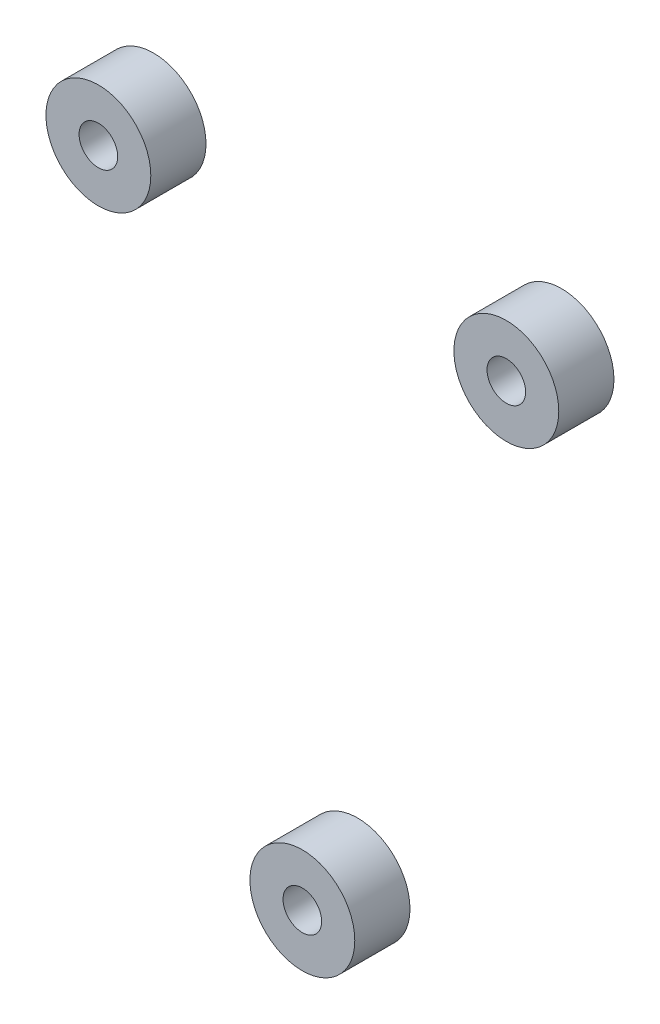
SolidWorks part; units mm, degrees
ref_plane "Front Plane" through (0, 0, 0) normal (0, 0, 1) x (1, 0, 0)
ref_plane "Top Plane" through (0, 0, 0) normal (0, 1, 0) x (1, 0, 0)
ref_plane "Right Plane" through (0, 0, 0) normal (1, 0, 0) x (0, 0, -1)
sketch "Sketch1" plane through (0, 0, 0) normal (0, 0, 1) x (1, 0, 0)
  line L0 (0, 57.5) -> (0, 0) construction
  line L1 (0, 0) -> (-36.9603, 44.0476) construction
  circle A1 centre (0, -57.5) radius 3.5
  circle A2 centre (0, 0) radius 57.5 construction
  circle A3 centre (-36.9603, 44.0476) radius 3.5
  circle A4 centre (36.9603, 44.0476) radius 3.5
  circle A5 centre (-36.9603, 44.0476) radius 9.5
  circle A6 centre (36.9603, 44.0476) radius 9.5
  circle A7 centre (0, -57.5) radius 9.5
  dimension "D1" = 7
  dimension "D2" = 115
  dimension "D3" = 40
  dimension "D4" = 6
extrude "Fog light screwholes" add sketch "Sketch1" along normal blind 10
